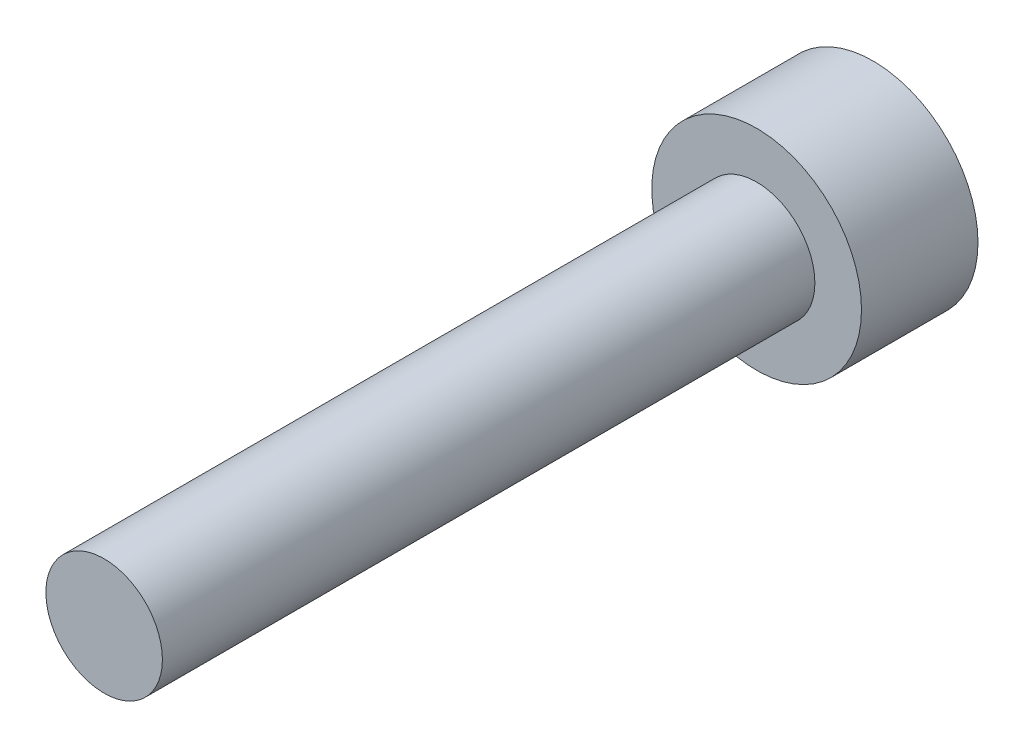
SolidWorks part; units mm, degrees
material "AISI 304"
ref_plane "Alzado" through (0, 0, 0) normal (0, 0, 1) x (1, 0, 0)
ref_plane "Planta" through (0, 0, 0) normal (0, 1, 0) x (1, 0, 0)
ref_plane "Vista lateral" through (0, 0, 0) normal (1, 0, 0) x (0, 0, -1)
sketch "Sk_Cabeza" plane through (0, 0, 0) normal (0, 0, 1) x (1, 0, 0)
  circle A0 centre (0, 0) radius 2.25
  dimension "D1" = 4.5
extrude "Cabeza" add sketch "Sk_Cabeza" along normal blind 2.5 from offset 2.5
sketch "Sk_Cuerpo" plane through (0, 0, 0) normal (0, 0, 1) x (1, 0, 0)
  circle A0 centre (0, 0) radius 1.25
  dimension "D1" = 2.5
extrude "Cuerpo" add sketch "Sk_Cuerpo" along normal blind 14
sketch "Sk_Hexagono_interior" plane through (0, 0, 0) normal (0, 0, 1) x (1, 0, 0)
  line L1 (0, -1.1547) -> (1, -0.5774)
  line L2 (1, -0.5774) -> (1, 0.5774)
  line L3 (1, 0.5774) -> (0, 1.1547)
  line L4 (0, 1.1547) -> (-1, 0.5774)
  line L5 (-1, 0.5774) -> (-1, -0.5774)
  line L6 (-1, -0.5774) -> (0, -1.1547)
  circle A0 centre (0, 0) radius 1 construction
  dimension "D1" = 2
extrude "Hexagono_interior" cut sketch "Sk_Hexagono_interior" along normal blind 1.25 from offset 2.5
